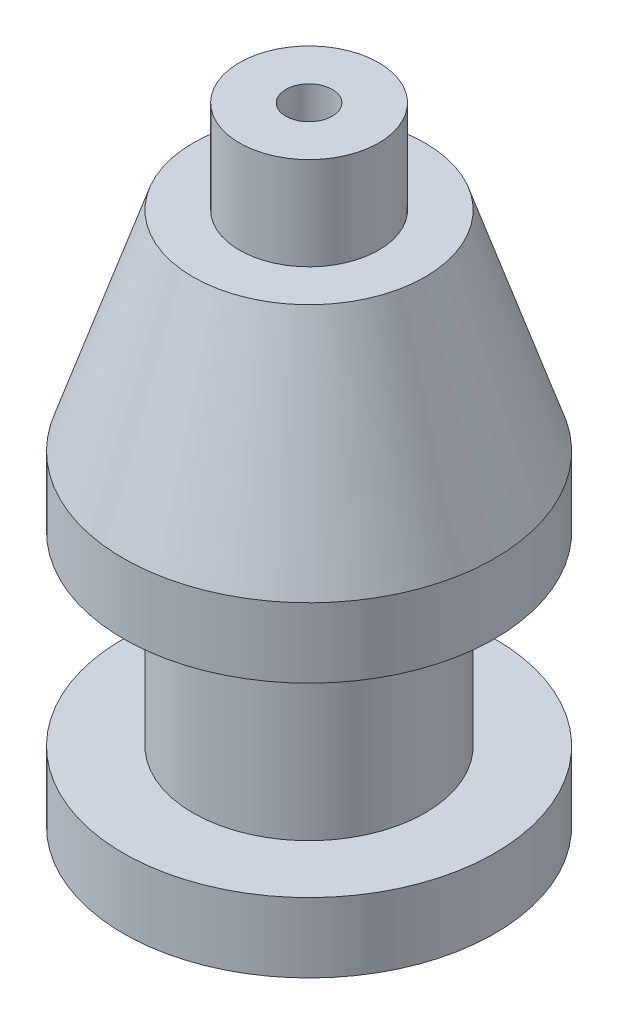
SolidWorks part; units mm, degrees
ref_plane "Front Plane" through (0, 0, 0) normal (0, 0, 1) x (1, 0, 0)
ref_plane "Top Plane" through (0, 0, 0) normal (0, 1, 0) x (1, 0, 0)
ref_plane "Right Plane" through (0, 0, 0) normal (1, 0, 0) x (0, 0, -1)
sketch "Sketch1" plane through (0, 0, 0) normal (0, 0, 1) x (1, 0, 0)
  line L0 (0, 0) -> (113528.8076, 0) construction
  line L1 (0, 0) -> (0, 113528.8076) construction
  line L2 (10, -110) -> (80, -110)
  line L3 (80, -110) -> (80, -80)
  line L4 (80, -80) -> (50, -80)
  line L5 (50, -80) -> (50, 0)
  line L6 (50, 0) -> (80, 0)
  line L7 (80, 0) -> (80, 30)
  line L8 (80, 30) -> (50, 120)
  line L9 (50, 120) -> (30, 120)
  line L10 (30, 120) -> (30, 160)
  line L11 (30, 160) -> (10, 160)
  line L12 (10, 160) -> (10, -110)
  point P15 (0, 0)
  point P17 (56.5283, 113.9548)
  point P18 (0, 0)
  dimension "D1" = 230
  dimension "D2" = 40
  dimension "D3" = 30
  dimension "D4" = 80
  dimension "D5" = 30
  dimension "D6" = 160
  dimension "D7" = 100
  dimension "D8" = 60
  dimension "D9" = 20
  dimension "D10" = 100
revolve "Revolve1" add sketch "Sketch1" angle 360 about L1
